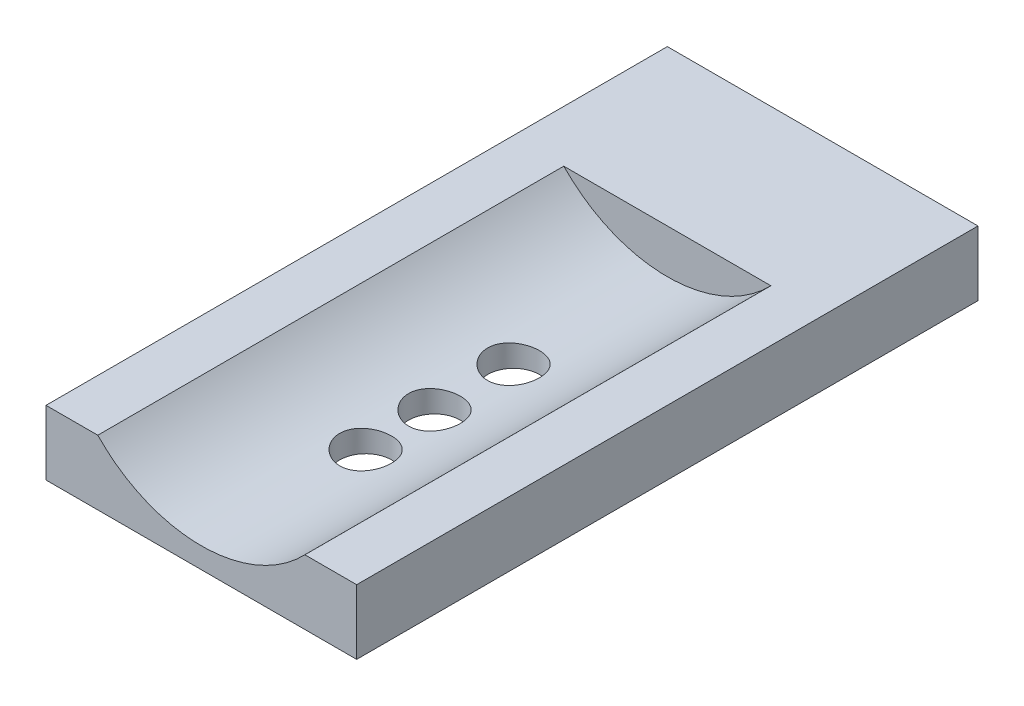
SolidWorks part; units mm, degrees
ref_plane "Front Plane" through (0, 0, 0) normal (0, 0, 1) x (1, 0, 0)
ref_plane "Top Plane" through (0, 0, 0) normal (0, 1, 0) x (1, 0, 0)
ref_plane "Right Plane" through (0, 0, 0) normal (1, 0, 0) x (0, 0, -1)
sketch "Sketch1" plane through (0, 0, 0) normal (1, 0, 0) x (0, 0, -1)
  line L0 (0, 0) -> (60, 0)
  line L1 (60, 0) -> (60, 6.25)
  line L2 (60, 6.25) -> (0, 6.25)
  line L3 (0, 6.25) -> (0, 0)
  line L4 (0, 3.125) -> (60, 3.125) construction
  dimension "D1" = 60
  dimension "D2" = 6.25
extrude "Boss-Extrude1" add sketch "Sketch1" along normal blind 30
sketch "Sketch2" plane through (0, 0, 0) normal (0, 0, 1) x (1, 0, 0)
  line L0 (30, 6.25) -> (0, 6.25) construction
  line L1 (5, 6.25) -> (25, 6.25)
  line L2 (5, 6.25) -> (25, 6.25)
  arc A0 (5, 6.25) -> (25, 6.25) centre (15, 15.8897) ccw
  point P3 (15, 2)
  dimension "D1" = 5
  dimension "D2" = 5
  dimension "D3" = 4.25
extrude "Cut-Extrude1" cut sketch "Sketch2" against normal blind 45 and the other way through all contours A0
sketch "Sketch4" plane through (0, 0, 0) normal (0, -1, 0) x (1, 0, 0)
  line L1 (22.8, -45.6) -> (22.8, -12.5)
  line L2 (22.8, -12.5) -> (7.2, -12.5)
  line L3 (7.2, -12.5) -> (7.2, -45.6)
  line L4 (30, -60) -> (0, -60) construction
  line L5 (22.8, -45.6) -> (22.8, -56.1)
  line L6 (7.2, -45.6) -> (22.8, -45.6)
  line L10 (22.8, -56.1) -> (7.2, -56.1)
  line L11 (7.2, -56.1) -> (7.2, -45.6)
  line L13 (30, 0) -> (0, 0) construction
  line L14 (25, -45) -> (5, -45) construction
  circle A0 centre (15, -15.87) radius 2.5
  circle A1 centre (15, -22.52) radius 2.5
  circle A2 centre (15, -30.15) radius 2.5
  point P7 (15, -60)
  point P12 (15, -12.5)
  point P20 (15, 0)
  dimension "D4" = 5
  dimension "D8" = 5
  dimension "D9" = 5
  dimension "D2" = 10.5
  dimension "D3" = 11.1
  dimension "D7" = 15.6
  dimension "D10" = 3.37
  dimension "D11" = 10.02
  dimension "D12" = 17.65
extrude "Cut-Extrude2" cut sketch "Sketch4" against normal blind 4
sketch "Sketch5" plane through (0, 0, -60) normal (0, 0, -1) x (-1, 0, 0)
  line L9 (-30, 0) -> (0, 0) construction
  line L10 (-30, 6.25) -> (0, 6.25) construction
  line L13 (-10, 1.25) -> (-20, 1.25)
  line L15 (-20, 4.25) -> (-10, 4.25)
  line L18 (-10, 4.25) -> (-10, 1.25)
  line L19 (-20, 1.25) -> (-18.5, 2.75)
  line L20 (-18.5, 2.75) -> (-20, 4.25)
  point P5 (-15, 1.25)
  point P10 (-15, 0)
  point P11 (-18.4784, 2.75)
  point P12 (-10, 2.75)
  dimension "D1" = 10
  dimension "D3" = 3
  dimension "D4" = 2
extrude "Cut-Extrude3" cut sketch "Sketch5" against normal up to vertex (3.9 mm away)
